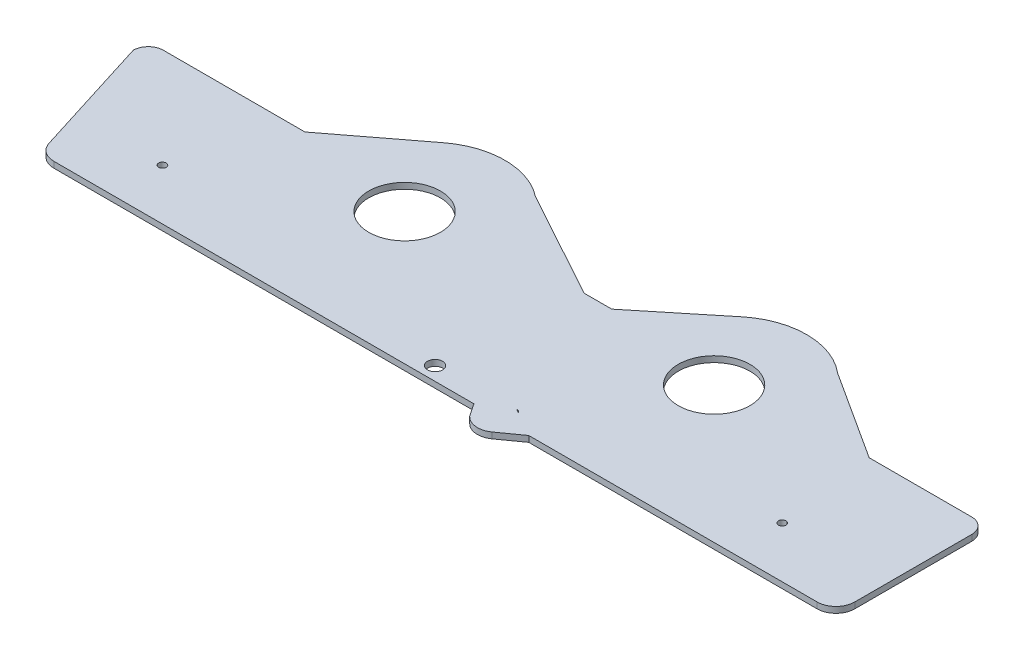
SolidWorks part; units mm, degrees
ref_plane "Front" through (0, 0, 0) normal (0, 0, 1) x (1, 0, 0)
ref_plane "Top" through (0, 0, 0) normal (0, 1, 0) x (1, 0, 0)
ref_plane "Right" through (0, 0, 0) normal (1, 0, 0) x (0, 0, -1)
sketch "Sketch1" plane through (0, 0, 0) normal (0, 1, 0) x (1, 0, 0)
  line L0 (0, 142) -> (42, 8)
  line L1 (0, 0) -> (444.5, 0)
  line L2 (0, 0) -> (0, 150)
  line L3 (0, 150) -> (444.5, 150)
  line L4 (444.5, 0) -> (444.5, 150)
  circle A0 centre (8, 142) radius 8
  circle A1 centre (50, 8) radius 8
  circle A2 centre (436.5, 142) radius 8
  circle A3 centre (436.5, 8) radius 8
  circle A5 centre (265.2813, 74.5639) radius 4.6
  circle A6 centre (172.5, 148.3404) radius 1.7
  dimension "D3" = 8
  dimension "D5" = 8
  dimension "D7" = 8
  dimension "D9" = 8
  dimension "D1" = 150
  dimension "D2" = 444.5
  dimension "D4" = 8
  dimension "D6" = 50
  dimension "D8" = 8
  dimension "D10" = 8
extrude "Boss-Extrude1" add sketch "Sketch1" along normal blind 3.175 contours A3 L4 A2 L3 A0 L0 A1 L1 | A1 | A0 L0 | A2 | A3
sketch "Sketch2" plane through (0, 0, 0) normal (0, 0, 1) x (1, 0, 0)
  line L1 (-78.5546, 38.0306) -> (518.9117, 38.0306)
  line L2 (-78.5546, 38.0306) -> (-78.5546, -22.9419)
  line L3 (-78.5546, -22.9419) -> (518.9117, -22.9419)
  line L4 (518.9117, 38.0306) -> (518.9117, -22.9419)
extrude "Cut-Extrude1" cut sketch "Sketch2" against normal blind 70
fillet "Fillet1" radius 10 1 edges at (22.5672, 1.5875, -70)
fillet "Fillet2" radius 10 1 edges at (444.5, 1.5875, -70)
sketch "Sketch3" plane through (0, 3.175, 0) normal (0, 1, 0) x (1, 0, 0)
  line L0 (444.5, 80) -> (444.5, 142) construction
  line L1 (29.9125, 70) -> (264.7058, 70) construction
  circle A0 centre (224.75, 77.255) radius 3.9908
  dimension "D1" = 219.75
  dimension "D2" = 7.255
extrude "Cut-Extrude2" cut sketch "Sketch3" against normal blind 10
sketch "Sketch4" plane through (0, 3.175, 0) normal (0, 1, 0) x (1, 0, 0)
  line L0 (29.9125, 70) -> (264.7058, 70) construction
  line L1 (444.5, 80) -> (444.5, 142) construction
  circle A0 centre (60.5, 97) radius 2
  dimension "D3" = 4
  dimension "D1" = 27
  dimension "D2" = 384
extrude "Cut-Extrude3" cut sketch "Sketch4" against normal through all
sketch "Sketch5" plane through (0, 3.175, 0) normal (0, 1, 0) x (1, 0, 0)
  line L0 (444.5, 80) -> (444.5, 142) construction
  line L1 (29.9125, 70) -> (264.7058, 70) construction
  circle A0 centre (389, 97) radius 2
  dimension "D1" = 55.5
  dimension "D3" = 4
  dimension "D2" = 27
extrude "Cut-Extrude4" cut sketch "Sketch5" against normal blind 10
sketch "Sketch6" plane through (0, 0, 0) normal (0, 1, 0) x (1, 0, 0)
  circle A0 centre (149, 150.0404) radius 40
  dimension "D1" = 80
  dimension "D2" = 141
extrude "Boss-Extrude2" add sketch "Sketch6" along normal blind 3.175
sketch "Sketch7" plane through (0, 0, 0) normal (0, 1, 0) x (1, 0, 0)
  line L0 (124.1645, 181.3964) -> (82.7029, 149.7505)
  line L1 (173.8355, 181.3964) -> (231.4689, 149.7505)
  line L2 (82.7029, 149.7505) -> (231.4689, 149.7505)
  line L3 (124.1645, 181.3964) -> (173.8355, 181.3964)
  arc A0 (189, 150) -> (109, 150) centre (149, 150.0404) ccw construction
extrude "Boss-Extrude3" add sketch "Sketch7" along normal blind 3.175
sketch "Sketch9" plane through (0, 0, 0) normal (0, 1, 0) x (1, 0, 0)
  line L0 (444.5, 80) -> (444.5, 142) construction
  line L1 (231.0146, 150) -> (436.5, 150) construction
  line L2 (283.7342, 181.0103) -> (245.6734, 150)
  line L3 (245.6734, 150) -> (269, 150)
  line L4 (334.2658, 181.0103) -> (397.5744, 150)
  circle A0 centre (309, 150) radius 40
  dimension "D1" = 135.5
  dimension "D2" = 0
extrude "Boss-Extrude4" add sketch "Sketch9" along normal blind 3.175 contours A0 L2 L3 | A0
sketch "Sketch12" plane through (0, 0, 0) normal (0, 1, 0) x (1, 0, 0)
  line L0 (326.1663, 186.1292) -> (382.1065, 150)
  line L1 (349, 150) -> (436.5, 150) construction
  line L2 (382.1065, 150) -> (340.3988, 150)
  line L3 (340.3988, 150) -> (326.1663, 186.1292)
  arc A0 (349, 150) -> (283.7342, 181.0103) centre (309, 150) ccw construction
extrude "Boss-Extrude6" add sketch "Sketch12" along normal blind 3.175
sketch "Sketch13" plane through (0, 3.175, 0) normal (0, 1, 0) x (1, 0, 0)
  circle A0 centre (146, 139.8404) radius 19
  arc A1 (173.8355, 181.3964) -> (124.1645, 181.3964) centre (149, 150.0404) ccw construction
  point P5 (149, 190.0404)
  dimension "D1" = 50.2
  dimension "D3" = 38
  dimension "D2" = 138
extrude "Cut-Extrude5" cut sketch "Sketch13" against normal blind 10
sketch "Sketch14" plane through (0, 3.175, 0) normal (0, 1, 0) x (1, 0, 0)
  circle A0 centre (307.6065, 142.2981) radius 19
  arc A2 (334.871, 180.5072) -> (283.7342, 181.0103) centre (309, 150) ccw construction
  point P6 (309.3935, 189.9981)
  dimension "D1" = 74.5
  dimension "D3" = 38
  dimension "D2" = 47.7
extrude "Cut-Extrude6" cut sketch "Sketch14" against normal blind 10
sketch "Sketch15" plane through (0, 3.175, 0) normal (0, 1, 0) x (1, 0, 0)
  line L0 (444.5, 80) -> (444.5, 142) construction
  line L2 (231.0146, 150) -> (245.6734, 150) construction
  line L3 (281.6714, 70) -> (270.3236, 61.8707)
  line L4 (29.9125, 70) -> (264.7058, 70) construction
  line L5 (264.5, 80) -> (251.9232, 70.9902)
  line L6 (264.5, 80) -> (281.6714, 70)
  line L7 (251.9232, 70.9902) -> (257.164, 63.2042)
  circle A0 centre (264.5, 70) radius 10
  dimension "D1" = 180
  dimension "D3" = 20
  dimension "D2" = 80
extrude "Boss-Extrude7" add sketch "Sketch15" along normal blind 10 and the other way blind 3.175
sketch "Sketch16" plane through (0, 13.175, 0) normal (0, 1, 0) x (1, 0, 0)
  line L1 (247.445, 85.003) -> (286.8256, 85.003)
  line L2 (247.445, 85.003) -> (247.445, 51.0981)
  line L3 (247.445, 51.0981) -> (286.8256, 51.0981)
  line L4 (286.8256, 85.003) -> (286.8256, 51.0981)
extrude "Cut-Extrude7" cut sketch "Sketch16" against normal blind 10
